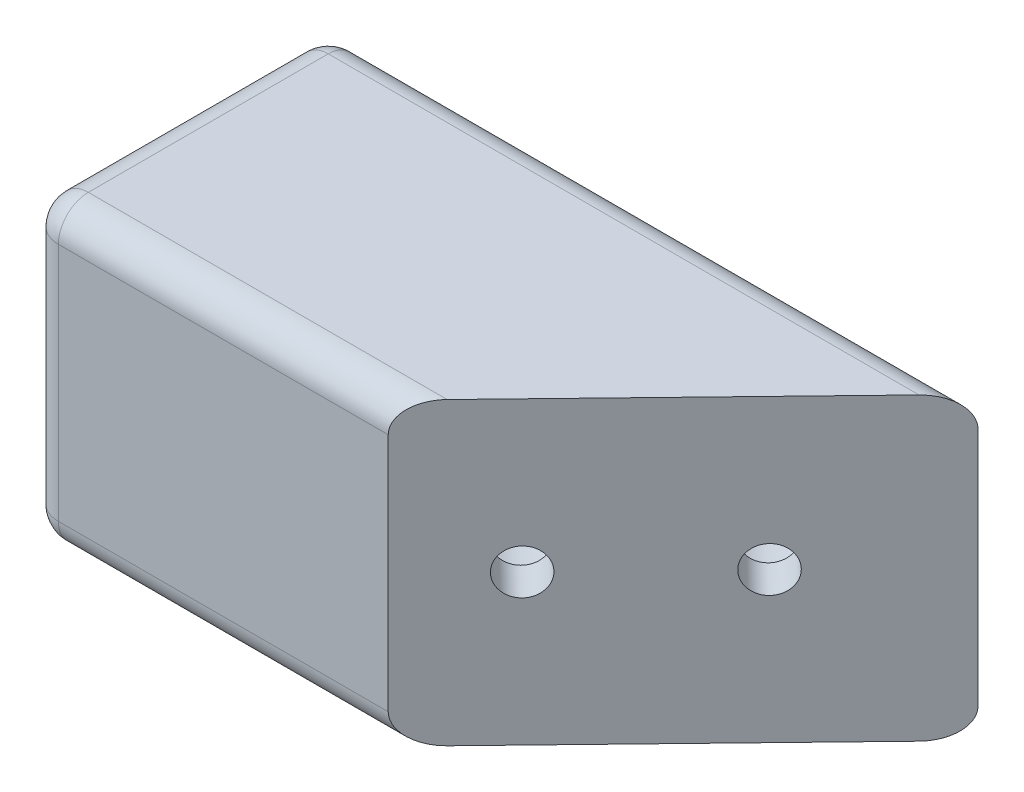
SolidWorks part; units mm, degrees
ref_plane "Front Plane" through (0, 0, 0) normal (0, 0, 1) x (1, 0, 0)
ref_plane "Top Plane" through (0, 0, 0) normal (0, 1, 0) x (1, 0, 0)
ref_plane "Right Plane" through (0, 0, 0) normal (1, 0, 0) x (0, 0, -1)
sketch "Sketch1" plane through (0, 0, 0) normal (0, 1, 0) x (1, 0, 0)
  line L0 (3.5, -15) -> (32.5, 15)
  line L1 (-32.5, -15) -> (3.5, -15)
  line L2 (-32.5, -15) -> (-32.5, 15)
  line L3 (-32.5, 15) -> (32.5, 15)
  point P0 (0, 0)
  point P4 (0, 0)
  point P6 (3.5, -15)
  dimension "D1" = 30
  dimension "D2" = 65
  dimension "D3" = 36
  dimension "D4" = 32.5
  dimension "D5" = 15
extrude "Boss-Extrude1" add sketch "Sketch1" along normal blind 30
sketch "Sketch2" plane through (9.305, 0, 8.9948) normal (0.719, 0, 0.695) x (0.695, 0, -0.719)
  line L0 (33.373, 30) -> (33.373, 0) construction
  line L1 (-8.3522, 0) -> (33.373, 0) construction
  circle A0 centre (18.623, 15) radius 2.25
  circle A1 centre (1.123, 15) radius 2.25
  dimension "D1" = 4.5
  dimension "D2" = 4.5
  dimension "D3" = 14.75
  dimension "D4" = 17.5
  dimension "D5" = 15
extrude "Cut-Extrude1" cut sketch "Sketch2" against normal through all
ref_plane "Plane1" through (6.429, 0, 6.2147) normal (0.719, 0, 0.695) x (0.695, 0, -0.719)
sketch "Sketch3" plane through (6.429, 0, 6.2147) normal (0.719, 0, 0.695) x (0.695, 0, -0.719)
  circle A0 centre (18.623, 15) radius 5
  circle A1 centre (1.123, 15) radius 5
  dimension "D1" = 10
  dimension "D2" = 10
extrude "Cut-Extrude2" cut sketch "Sketch3" against normal through all
fillet "Fillet1" radius 3 8 edges at (-14.5, 0, 15) (-14.5, 30, 15) (-32.5, 15, 15) (-32.5, 0, 0) (0, 0, -15) (-32.5, 15, -15) (-32.5, 30, 0) (0, 30, -15)
